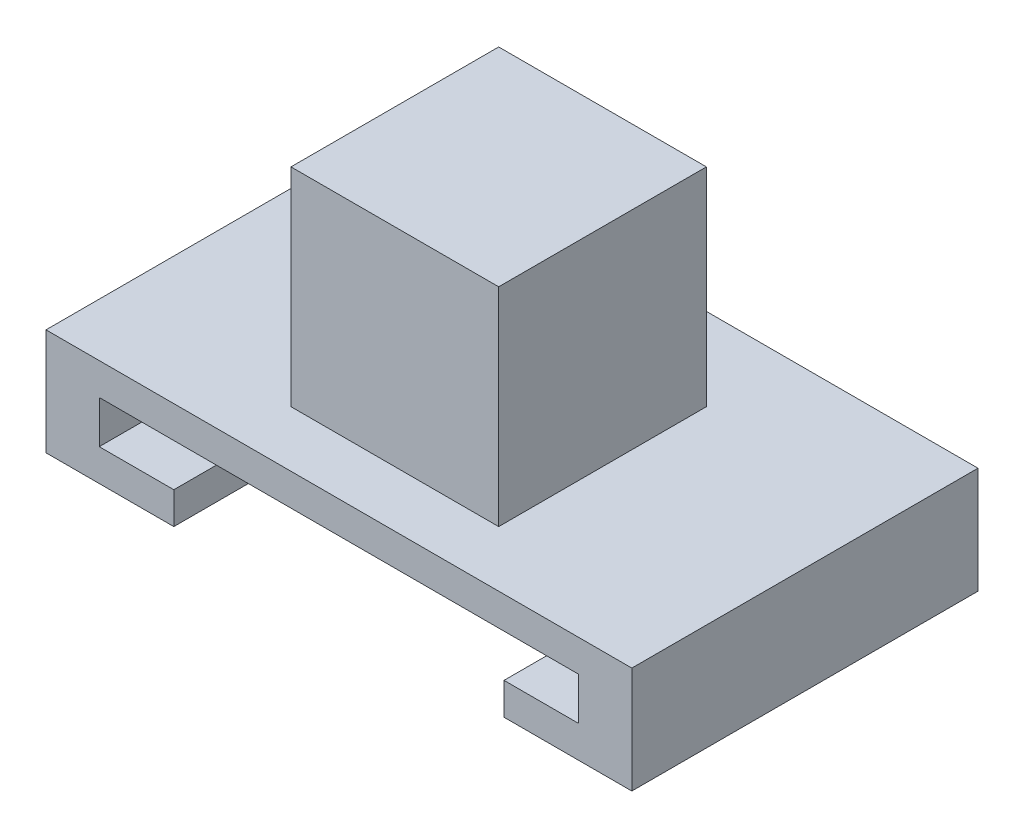
SolidWorks part; units mm, degrees
ref_plane "Front Plane" through (0, 0, 0) normal (0, 0, 1) x (1, 0, 0)
ref_plane "Top Plane" through (0, 0, 0) normal (0, 1, 0) x (1, 0, 0)
ref_plane "Right Plane" through (0, 0, 0) normal (1, 0, 0) x (0, 0, -1)
sketch "Sketch1" plane through (0, 0, 0) normal (0, 0, 1) x (1, 0, 0)
  line L0 (12, 0) -> (12, 3)
  line L1 (0, 0) -> (12, 0)
  line L2 (0, 0) -> (0, 10)
  line L3 (0, 10) -> (55, 10)
  line L5 (12, 3) -> (5, 3)
  line L6 (5, 3) -> (5, 7)
  line L7 (5, 7) -> (50, 7)
  line L8 (50, 3) -> (50, 7)
  line L9 (43, 3) -> (50, 3)
  line L10 (55, 0) -> (55, 10)
  line L11 (55, 0) -> (43, 0)
  line L12 (43, 0) -> (43, 3)
  dimension "D2" = 10
  dimension "D4" = 4
  dimension "D5" = 5
  dimension "D6" = 12
extrude "Boss-Extrude1" add sketch "Sketch1" along normal blind 30
sketch "Sketch2" plane through (0, 10, 0) normal (0, 1, 0) x (1, 0, 0)
  line L0 (55, 0) -> (0, 0) construction
  line L1 (17.75, -5.25) -> (37.25, -5.25)
  line L2 (17.75, -5.25) -> (17.75, -24.75)
  line L3 (17.75, -24.75) -> (37.25, -24.75)
  line L4 (37.25, -5.25) -> (37.25, -24.75)
  line L5 (55, -30) -> (55, 0) construction
  dimension "D1" = 19.5
  dimension "D2" = 19.5
  dimension "D3" = 5.25
  dimension "D4" = 17.75
extrude "Boss-Extrude2" add sketch "Sketch2" along normal blind 19.5
sketch "Sketch3" plane through (0, 0, 0) normal (0, 0, -1) x (-1, 0, 0)
  line L1 (-55, 10) -> (0, 10)
  line L2 (-55, 10) -> (-55, 0)
  line L3 (-55, 0) -> (0, 0)
  line L4 (0, 10) -> (0, 0)
extrude "Boss-Extrude3" add sketch "Sketch3" along normal blind 2.5
